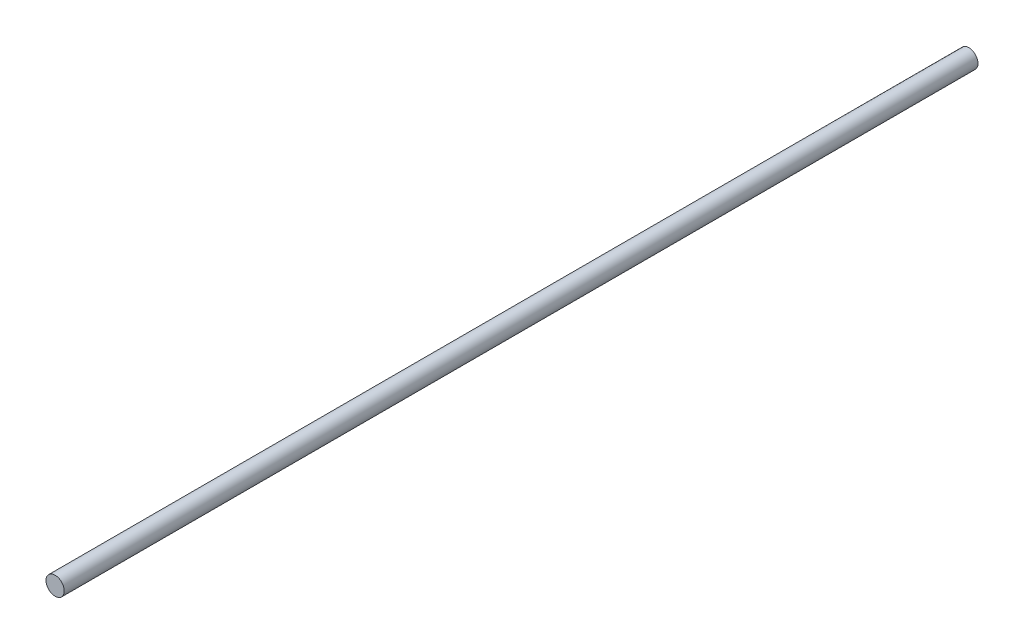
SolidWorks part; units mm, degrees
ref_plane "Front Plane" through (0, 0, 0) normal (0, 0, 1) x (1, 0, 0)
ref_plane "Top Plane" through (0, 0, 0) normal (0, 1, 0) x (1, 0, 0)
ref_plane "Right Plane" through (0, 0, 0) normal (1, 0, 0) x (0, 0, -1)
sketch "Эскиз1" plane through (0, 0, 0) normal (0, 0, 1) x (1, 0, 0)
  circle A0 centre (0, 0) radius 10
  dimension "D1" = 20
extrude "Бобышка-Вытянуть1" add sketch "Эскиз1" along normal mid plane 1000
